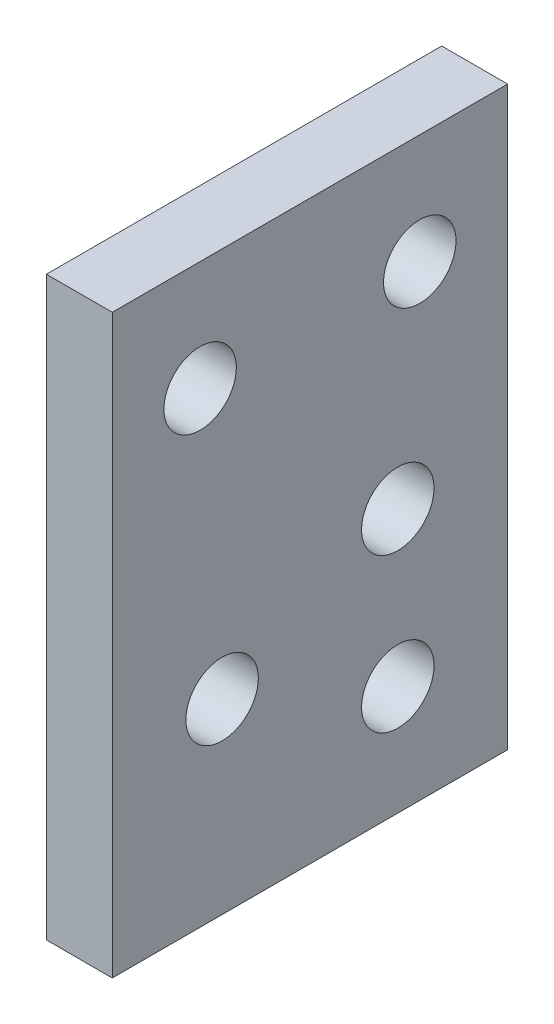
SolidWorks part; units mm, degrees
material "Thornel Mat VMA"
ref_plane "前视基准面" through (0, 0, 0) normal (0, 0, 1) x (1, 0, 0)
ref_plane "上视基准面" through (0, 0, 0) normal (0, 1, 0) x (1, 0, 0)
ref_plane "右视基准面" through (0, 0, 0) normal (1, 0, 0) x (0, 0, -1)
sketch "草图1" plane through (0, 0, 0) normal (1, 0, 0) x (0, 0, -1)
  line L0 (4, -1.125) -> (4, -8.125) construction
  line L1 (9, -13.125) -> (-9, -13.125)
  line L2 (9, -13.125) -> (9, 13.125)
  line L3 (9, 13.125) -> (-9, 13.125)
  line L4 (-9, -13.125) -> (-9, 13.125)
  line L5 (9, -13.125) -> (-9, 13.125) construction
  line L6 (9, 13.125) -> (-9, -13.125) construction
  line L7 (-4, -4.625) -> (4, -4.625) construction
  line L8 (0, 17.375) -> (0, 0) construction
  line L9 (0, 3.125) -> (12.0722, 3.125) construction
  line L10 (5, 4.375) -> (-12.2737, 4.375) construction
  circle A0 centre (4, -1.125) radius 1.65
  circle A1 centre (4, -8.125) radius 1.65
  circle A2 centre (-4, -4.625) radius 1.65
  circle A3 centre (0, 8.125) radius 1.65 construction
  circle A4 centre (0, -1.875) radius 1.65 construction
  circle A5 centre (-5, 8.125) radius 1.65
  circle A6 centre (5, 8.125) radius 1.65
  point P0 (0, 0)
  dimension "D2" = 3.3
  dimension "D6" = 4
  dimension "D7" = 5
  dimension "D1" = 17.75
  dimension "D3" = 7
  dimension "D4" = 8
  dimension "D5" = 5
  dimension "D8" = 10
  dimension "D9" = 10
  dimension "D10" = 10
  dimension "D11" = 9
  dimension "D12" = 5
extrude "凸台-拉伸1" add sketch "草图1" along normal blind 3
